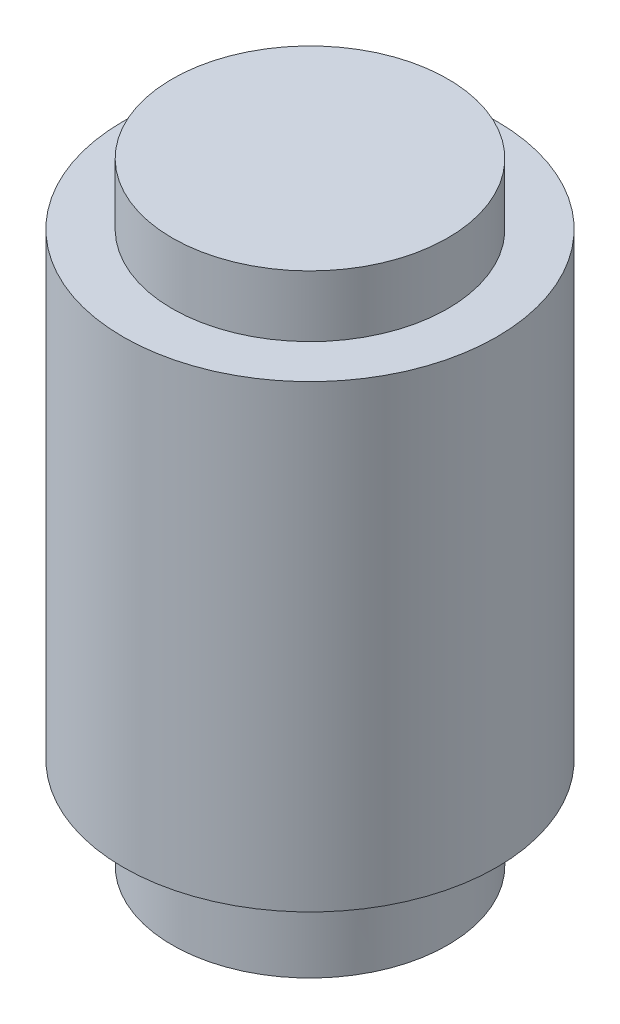
SolidWorks part; units mm, degrees
material "ABS"
ref_plane "Alzado" through (0, 0, 0) normal (0, 0, 1) x (1, 0, 0)
ref_plane "Planta" through (0, 0, 0) normal (0, 1, 0) x (1, 0, 0)
ref_plane "Vista lateral" through (0, 0, 0) normal (1, 0, 0) x (0, 0, -1)
sketch "Croquis1" plane through (0, 0, 0) normal (0, 1, 0) x (1, 0, 0)
  circle A0 centre (0, 0) radius 22.5
  dimension "D1" = 45
extrude "Saliente-Extruir1" add sketch "Croquis1" along normal blind 110
sketch "Croquis2" plane through (0, 0, 0) normal (0, -1, 0) x (1, 0, 0)
  circle A0 centre (0, 0) radius 16.7
  circle A1 centre (0, 0) radius 13.3
  dimension "D1" = 33.4
  dimension "D2" = 3.4
extrude "Cortar-Extruir1" cut sketch "Croquis2" against normal offset from surface (90 mm away) 20 up to face at (0, 110, 22.5)
sketch "Croquis4" plane through (0, 0, 0) normal (0, -1, 0) x (1, 0, 0)
  circle A1 centre (0, 0) radius 22.5
  circle A2 centre (0, 0) radius 22.5
  dimension "D1" = 0
extrude "Cortar-Extruir2" cut sketch "Croquis4" against normal blind 10
ref_plane "Plano1" through (0, 100, 0) normal (0, 1, 0) x (1, 0, 0)
sketch "Croquis5" plane through (0, 100, 0) normal (0, 1, 0) x (1, 0, 0)
  circle A0 centre (0, 0) radius 30.5
  circle A1 centre (0, 0) radius 22.5 construction
  circle A2 centre (0, 0) radius 22.5
  dimension "D1" = 8
extrude "Saliente-Extruir2" add sketch "Croquis5" against normal blind 75
